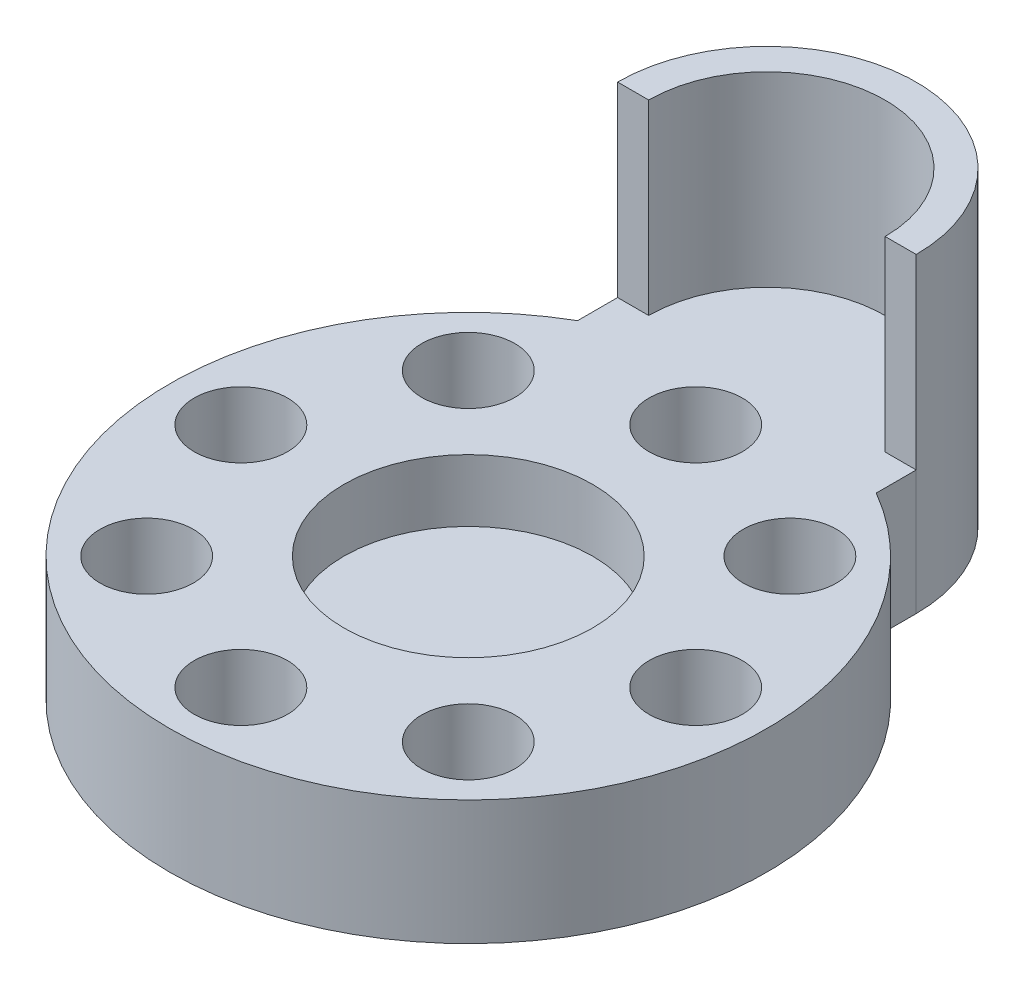
SolidWorks part; units mm, degrees
ref_plane "前基準面" through (0, 0, 0) normal (0, 0, 1) x (1, 0, 0)
ref_plane "上基準面" through (0, 0, 0) normal (0, 1, 0) x (1, 0, 0)
ref_plane "右基準面" through (0, 0, 0) normal (1, 0, 0) x (0, 0, -1)
sketch "草圖1" plane through (0, 0, 0) normal (0, 1, 0) x (1, 0, 0)
  line L0 (-24, 41.5692) -> (-24, 48)
  line L1 (0, 79.7392) -> (0, 28.388) construction
  line L2 (24, 41.5692) -> (24, 48)
  arc A0 (-24, 41.5692) -> (24, 41.5692) centre (0, 0) ccw
  arc A1 (24, 48) -> (-24, 48) centre (0, 48) ccw
  dimension "D1" = 96
  dimension "D2" = 24
  dimension "D3" = 48
extrude "填料-伸長1" add sketch "草圖1" along normal blind 20
sketch "草圖2" plane through (0, 20, 0) normal (0, 1, 0) x (1, 0, 0)
  circle A0 centre (0, 0) radius 20
  dimension "D1" = 40
extrude "除料-伸長1" cut sketch "草圖2" against normal blind 10
sketch "草圖3" plane through (0, 20, 0) normal (0, 1, 0) x (1, 0, 0)
  circle A0 centre (0, 0) radius 36.5531 construction
  circle A1 centre (0, 36.5531) radius 7.5
  circle A2 centre (25.847, 25.847) radius 7.5
  circle A3 centre (36.5531, 0) radius 7.5
  circle A4 centre (25.847, -25.847) radius 7.5
  circle A5 centre (0, -36.5531) radius 7.5
  circle A6 centre (-25.847, -25.847) radius 7.5
  circle A7 centre (-36.5531, 0) radius 7.5
  circle A8 centre (-25.847, 25.847) radius 7.5
  point P5 (0, 0)
  point P22 (0, 0)
  dimension "D2" = 15
  dimension "D1" = 8
extrude "除料-伸長2" cut sketch "草圖3" against normal through all
sketch "草圖4" plane through (0, 20, 0) normal (0, 1, 0) x (1, 0, 0)
  line L0 (-24, 48) -> (-19, 48)
  line L1 (19, 48) -> (24, 48)
  line L2 (24, 41.5692) -> (24, 48)
  line L3 (-24, 48) -> (-24, 41.5692)
  arc A0 (19, 48) -> (-19, 48) centre (0, 48) ccw
  arc A2 (-24, 41.5692) -> (24, 41.5692) centre (0, 0) ccw
  arc A3 (24, 48) -> (-24, 48) centre (0, 48) ccw
  arc A5 (24, 48) -> (-24, 48) centre (0, 48) ccw
  dimension "D1" = 0
  dimension "D2" = 5
extrude "填料-伸長2" add sketch "草圖4" along normal blind 30
